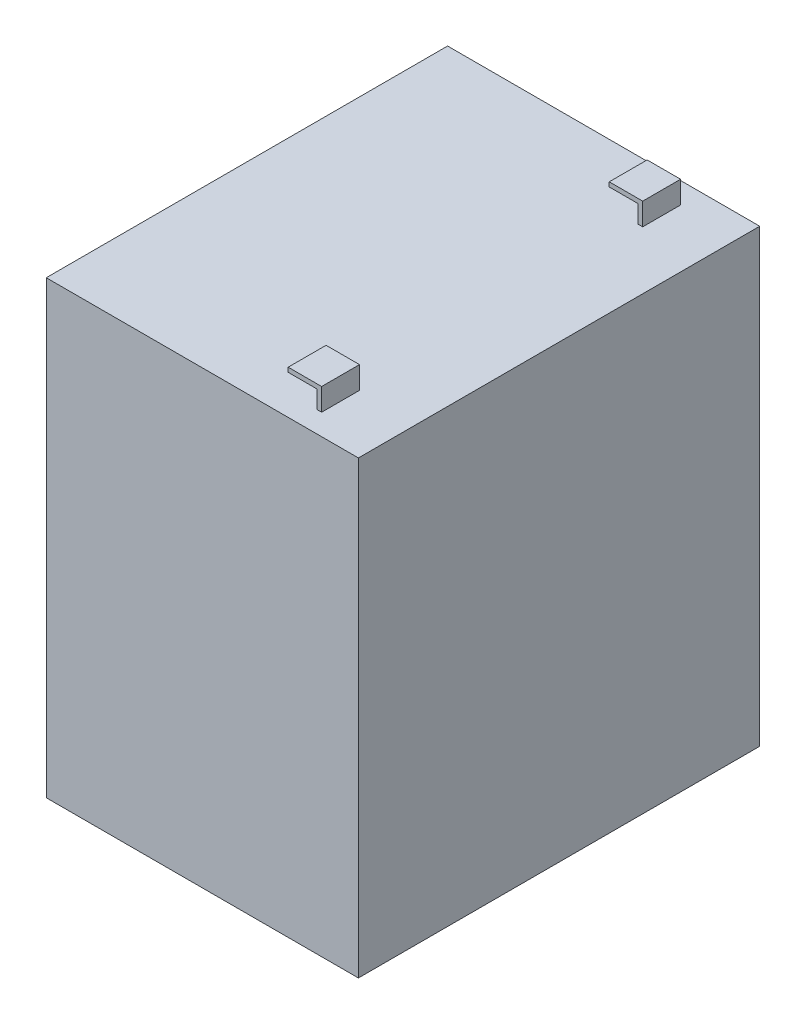
SolidWorks part; units mm, degrees
ref_plane "前视基准面" through (0, 0, 0) normal (0, 0, 1) x (1, 0, 0)
ref_plane "上视基准面" through (0, 0, 0) normal (0, 1, 0) x (1, 0, 0)
ref_plane "右视基准面" through (0, 0, 0) normal (1, 0, 0) x (0, 0, -1)
sketch "草图2" plane through (0, 0, 0) normal (0, 1, 0) x (1, 0, 0)
  line L0 (-99.9093, 0) -> (104.6669, 0) construction
  line L1 (-35, 45) -> (35, 45)
  line L2 (-35, 45) -> (-35, -45)
  line L3 (-35, -45) -> (35, -45)
  line L5 (0, 107.4782) -> (0, -102.2881) construction
  line L8 (35, 45) -> (35, -45)
  dimension "D1" = 90
  dimension "D2" = 70
extrude "拉伸1" add sketch "草图2" along normal blind 101
sketch "草图3" plane through (0, 101, 0) normal (0, 1, 0) x (1, 0, 0)
  line L0 (-57.1418, 0) -> (70.6472, 0) construction
  line L1 (0, 59.9459) -> (0, -66.9473) construction
  line L2 (43.9211, 36) -> (-38.6885, 36) construction
  line L3 (14.5, 40.25) -> (22, 40.25)
  line L4 (14.5, 40.25) -> (14.5, 31.75)
  line L5 (14.5, 31.75) -> (22, 31.75)
  line L6 (22, 40.25) -> (22, 31.75)
  line L7 (35, -45) -> (35, 45) construction
  line L8 (22, -40.25) -> (22, -31.75)
  line L9 (14.5, -31.75) -> (22, -31.75)
  line L10 (14.5, -40.25) -> (14.5, -31.75)
  line L11 (14.5, -40.25) -> (22, -40.25)
  dimension "D1" = 7.5
  dimension "D2" = 8.5
  dimension "D3" = 36
  dimension "D4" = 13
extrude "凸台-拉伸1" add sketch "草图3" along normal blind 5
sketch "草图4" plane through (0, 0, 40.25) normal (0, 0, 1) x (1, 0, 0)
  line L0 (14.5, 106) -> (22, 106) construction
  line L1 (14.5, 101) -> (21, 101)
  line L2 (14.5, 101) -> (14.5, 105)
  line L3 (14.5, 105) -> (21, 105)
  line L4 (21, 101) -> (21, 105)
  line L5 (22, 106) -> (22, 101) construction
  dimension "D1" = 1
  dimension "D2" = 1
extrude "切除-拉伸1" cut sketch "草图4" against normal through all
